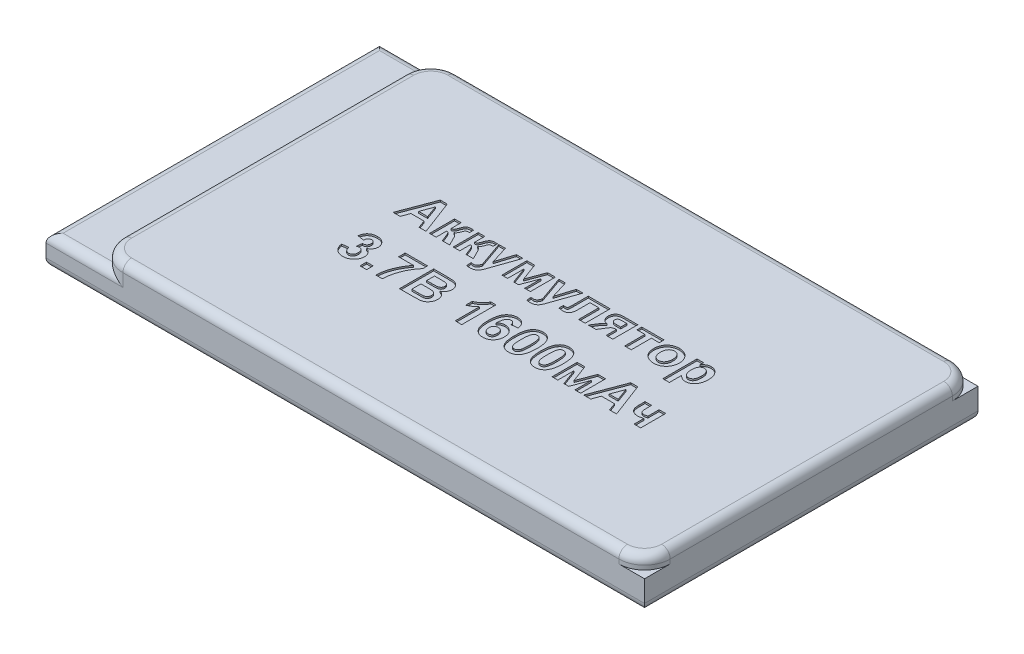
SolidWorks part; units mm, degrees
ref_plane "Спереди" through (0, 0, 0) normal (0, 0, 1) x (1, 0, 0)
ref_plane "Сверху" through (0, 0, 0) normal (0, 1, 0) x (1, 0, 0)
ref_plane "Справа" through (0, 0, 0) normal (1, 0, 0) x (0, 0, -1)
sketch "Эскиз1" plane through (0, 0, 0) normal (0, 1, 0) x (1, 0, 0)
  line L1 (-35, 19.5) -> (35, 19.5)
  line L2 (-35, 19.5) -> (-35, -19.5)
  line L3 (-35, -19.5) -> (35, -19.5)
  line L4 (35, 19.5) -> (35, -19.5)
  line L5 (-35, 19.5) -> (35, -19.5) construction
  line L6 (-35, -19.5) -> (35, 19.5) construction
  point P0 (0, 0)
  dimension "D1" = 39
  dimension "D2" = 70
extrude "Бобышка-Вытянуть1" add sketch "Эскиз1" along normal blind 3.5
sketch "Эскиз2" plane through (0, 3.5, 0) normal (0, 1, 0) x (1, 0, 0)
  line L0 (-35, -19.5) -> (35, -19.5) construction
  line L4 (32, 19.5) -> (-26, 19.5)
  line L5 (35, 16.5) -> (35, -16.5)
  line L6 (32, -19.5) -> (-26, -19.5)
  line L7 (-29, 16.5) -> (-29, -16.5)
  arc A0 (-29, -16.5) -> (-26, -19.5) centre (-26, -16.5) ccw
  arc A1 (32, -19.5) -> (35, -16.5) centre (32, -16.5) ccw
  arc A2 (35, 16.5) -> (32, 19.5) centre (32, 16.5) ccw
  arc A3 (-26, 19.5) -> (-29, 16.5) centre (-26, 16.5) ccw
  point P8 (-29, -19.5)
  point P14 (35, 19.5)
  dimension "D2" = 3
  dimension "D1" = 64
extrude "Бобышка-Вытянуть2" add sketch "Эскиз2" along normal blind 1.5
fillet "Скругление1" radius 1 15 edges at (0, 0, -19.5) (-35, 0, 0) (0, 0, 19.5) (35, 0, 0) (-29, 5, 0) (-28.1213, 5, -18.6213) (3, 5, -19.5) (34.1213, 5, -18.6213) (35, 5, 0) (34.1213, 5, 18.6213) (3, 5, 19.5) (-28.1213, 5, 18.6213) (-30.5, 3.5, -19.5) (-30.5, 3.5, 19.5) (-35, 3.5, 0)
sketch "Эскиз3" plane through (0, 5, 0) normal (0, 1, 0) x (1, 0, 0)
  text T0 "<b>Аккумулятор</b>\r\n<b>3.7В 1600мАч</b>"
extrude "Вырез-Вытянуть1" cut sketch "Эскиз3" against normal blind 0.2
